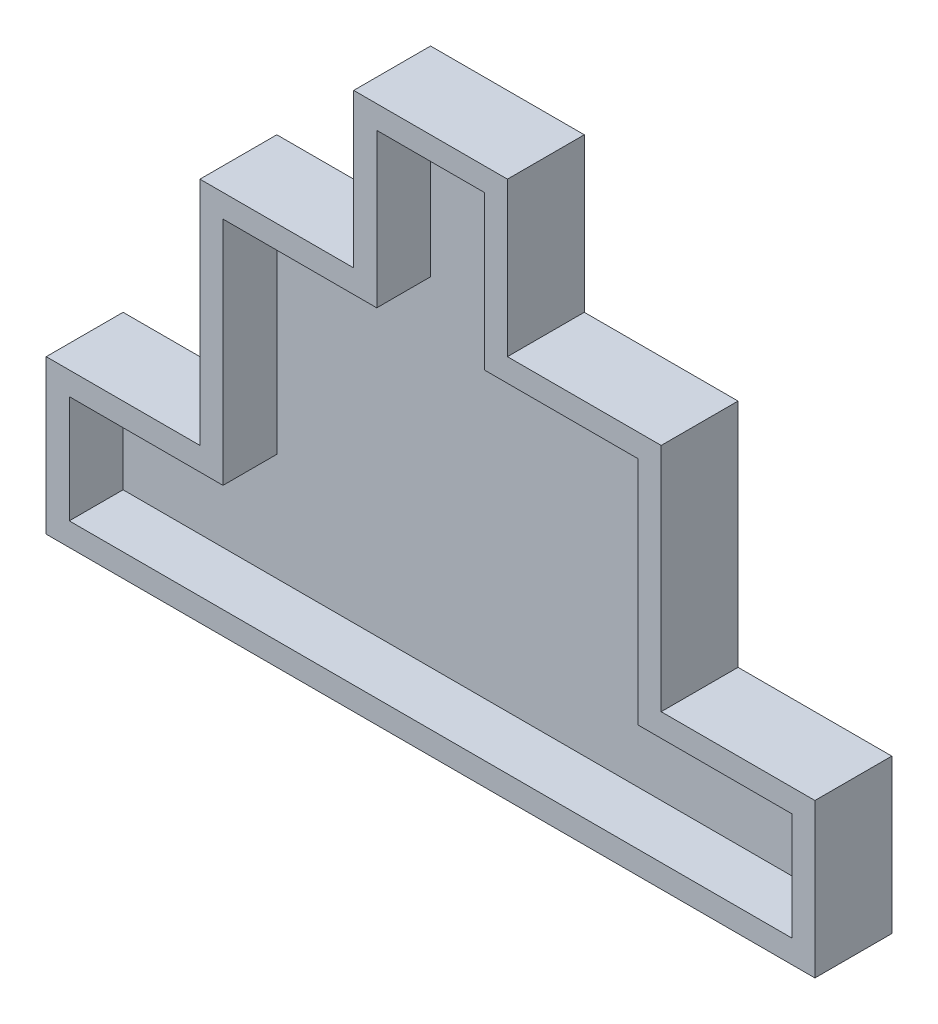
SolidWorks part; units mm, degrees
ref_plane "Front Plane" through (0, 0, 0) normal (0, 0, 1) x (1, 0, 0)
ref_plane "Top Plane" through (0, 0, 0) normal (0, 1, 0) x (1, 0, 0)
ref_plane "Right Plane" through (0, 0, 0) normal (1, 0, 0) x (0, 0, -1)
sketch "Sketch1" plane through (0, 0, 0) normal (0, 0, 1) x (1, 0, 0)
  line L0 (0, 0) -> (0, 157.9692) construction
  line L1 (-75, 15) -> (-45, 15)
  line L2 (-75, 15) -> (-75, -15)
  line L3 (-75, -15) -> (75, -15)
  line L4 (75, 15) -> (75, -15)
  line L5 (-75, 15) -> (75, -15) construction
  line L6 (-75, -15) -> (75, 15) construction
  line L7 (15, 60) -> (45, 60)
  line L8 (-45, 60) -> (-15, 60)
  line L9 (-45, 60) -> (-45, 15)
  line L11 (45, 60) -> (45, 15)
  line L12 (-45, 60) -> (45, 15) construction
  line L13 (-45, 15) -> (45, 60) construction
  line L14 (-15, 90) -> (15, 90)
  line L15 (-15, 90) -> (-15, 60)
  line L17 (15, 90) -> (15, 60)
  line L18 (-15, 90) -> (15, 60) construction
  line L19 (-15, 60) -> (15, 90) construction
  line L20 (45, 15) -> (75, 15)
  point P0 (0, 0)
  point P8 (0, 37.5)
  point P13 (0, 75)
  dimension "D1" = 30
  dimension "D2" = 150
  dimension "D3" = 30
  dimension "D4" = 45
  dimension "D5" = 30
  dimension "D6" = 90
extrude "Boss-Extrude2" add sketch "Sketch1" along normal blind 4.5
sketch "Sketch2" plane through (0, 0, 4.5) normal (0, 0, 1) x (1, 0, 0)
  line L82 (15, 90) -> (-15, 90)
  line L83 (-15, 90) -> (-15, 60)
  line L84 (-15, 60) -> (-45, 60)
  line L85 (-45, 60) -> (-45, 15)
  line L86 (-45, 15) -> (-75, 15)
  line L87 (-75, 15) -> (-75, -15)
  line L88 (-75, -15) -> (75, -15)
  line L89 (75, -15) -> (75, 15)
  line L90 (75, 15) -> (45, 15)
  line L91 (45, 15) -> (45, 60)
  line L92 (45, 60) -> (15, 60)
  line L93 (15, 60) -> (15, 90)
  line L94 (10.5, 55.5) -> (10.5, 85.5)
  line L95 (40.5, 55.5) -> (10.5, 55.5)
  line L96 (40.5, 10.5) -> (40.5, 55.5)
  line L97 (70.5, 10.5) -> (40.5, 10.5)
  line L98 (70.5, -10.5) -> (70.5, 10.5)
  line L99 (-70.5, -10.5) -> (70.5, -10.5)
  line L100 (-70.5, 10.5) -> (-70.5, -10.5)
  line L101 (-40.5, 10.5) -> (-70.5, 10.5)
  line L102 (-10.5, 55.5) -> (-40.5, 55.5)
  line L103 (-40.5, 55.5) -> (-40.5, 10.5)
  line L104 (-10.5, 85.5) -> (-10.5, 55.5)
  line L105 (10.5, 85.5) -> (-10.5, 85.5)
  line L106 (10.5, 55.5) -> (10.5, 85.5)
  line L107 (40.5, 55.5) -> (10.5, 55.5)
  line L108 (40.5, 10.5) -> (40.5, 55.5)
  line L109 (70.5, 10.5) -> (40.5, 10.5)
  line L110 (70.5, -10.5) -> (70.5, 10.5)
  line L111 (-70.5, -10.5) -> (70.5, -10.5)
  line L112 (-70.5, 10.5) -> (-70.5, -10.5)
  line L113 (-40.5, 10.5) -> (-70.5, 10.5)
  line L114 (-10.5, 55.5) -> (-40.5, 55.5)
  line L115 (-40.5, 55.5) -> (-40.5, 10.5)
  line L116 (-10.5, 85.5) -> (-10.5, 55.5)
  line L117 (10.5, 85.5) -> (-10.5, 85.5)
  dimension "D1" = 4.5
  dimension "D2" = 4.5
extrude "Boss-Extrude3" add sketch "Sketch2" along normal blind 10.5
